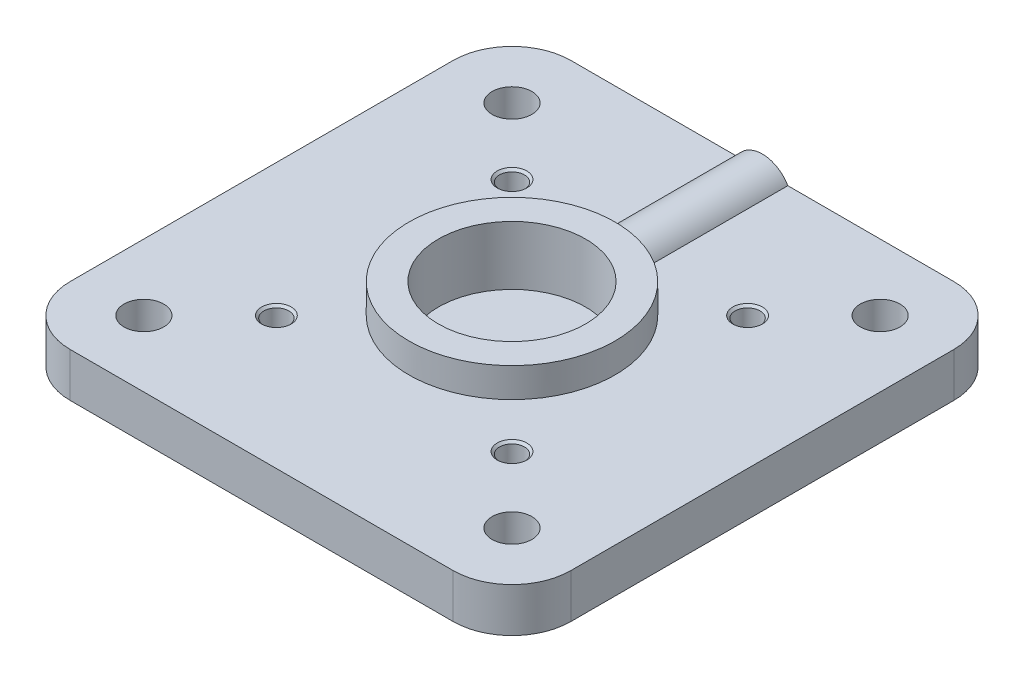
SolidWorks part; units mm, degrees
material "1060 Сплав"
ref_plane "Спереди" through (0, 0, 0) normal (0, 0, 1) x (1, 0, 0)
ref_plane "Сверху" through (0, 0, 0) normal (0, 1, 0) x (1, 0, 0)
ref_plane "Справа" through (0, 0, 0) normal (1, 0, 0) x (0, 0, -1)
sketch "Эскиз1" plane through (0, 0, 0) normal (0, 1, 0) x (1, 0, 0)
  line L1 (-65, -85) -> (65, -85)
  line L2 (-85, -65) -> (-85, 65)
  line L3 (-65, 85) -> (65, 85)
  line L4 (85, -65) -> (85, 65)
  line L5 (-85, -85) -> (85, 85) construction
  line L6 (-85, 85) -> (85, -85) construction
  arc A0 (-85, -65) -> (-65, -85) centre (-65, -65) ccw
  arc A1 (65, -85) -> (85, -65) centre (65, -65) ccw
  arc A2 (85, 65) -> (65, 85) centre (65, 65) ccw
  arc A3 (-65, 85) -> (-85, 65) centre (-65, 65) ccw
  point P0 (0, 0)
  dimension "D2" = 20
  dimension "D1" = 170
extrude "Бобышка-Вытянуть1" add sketch "Эскиз1" along normal blind 15
sketch "Эскиз2" plane through (0, 15, 0) normal (0, 1, 0) x (1, 0, 0)
  circle A0 centre (0, 0) radius 35
  dimension "D1" = 70
extrude "Бобышка-Вытянуть2" add sketch "Эскиз2" along normal blind 10
sketch "Эскиз3" plane through (0, 0, 0) normal (0, -1, 0) x (1, 0, 0)
  circle A0 centre (0, 0) radius 65
  circle A1 centre (0, 0) radius 50
  dimension "D1" = 130
  dimension "D2" = 100
extrude "Бобышка-Вытянуть3" add sketch "Эскиз3" along normal blind 10
sketch "Эскиз4" plane through (0, 25, 0) normal (0, 1, 0) x (1, 0, 0)
  circle A0 centre (0, 0) radius 25
  dimension "D1" = 50
extrude "Вырез-Вытянуть1" cut sketch "Эскиз4" against normal blind 20
sketch "Эскиз5" plane through (0, 15, 0) normal (0, 1, 0) x (1, 0, 0)
  line L1 (-62.5, -62.5) -> (62.5, -62.5) construction
  line L2 (-62.5, -62.5) -> (-62.5, 62.5) construction
  line L3 (-62.5, 62.5) -> (62.5, 62.5) construction
  line L4 (62.5, -62.5) -> (62.5, 62.5) construction
  line L5 (-62.5, -62.5) -> (62.5, 62.5) construction
  line L6 (-62.5, 62.5) -> (62.5, -62.5) construction
  circle A0 centre (-62.5, 62.5) radius 6.75
  circle A1 centre (62.5, 62.5) radius 6.75
  circle A2 centre (62.5, -62.5) radius 6.75
  circle A3 centre (-62.5, -62.5) radius 6.75
  point P0 (0, 0)
  dimension "D2" = 13.5
  dimension "D1" = 125
extrude "Вырез-Вытянуть2" cut sketch "Эскиз5" against normal up to next
sketch "Эскиз9" plane through (0, 0, -85) normal (0, 0, -1) x (-1, 0, 0)
  line L0 (0, -1000) -> (0, 49000) construction
  line L1 (-65, 0) -> (65, 0) construction
  circle A0 centre (0, 10) radius 10
  point P5 (0, 0)
  dimension "D1" = 20
extrude "Бобышка-Вытянуть4" add sketch "Эскиз9" against normal up to next
sketch "Эскиз10" plane through (0, 0, -85) normal (0, 0, -1) x (-1, 0, 0)
  line L0 (0, -1000) -> (0, 49000) construction
  line L1 (-65, 0) -> (65, 0) construction
  line L2 (-65, 0) -> (65, 0) construction
  circle A0 centre (0, 10) radius 6
  point P5 (0, 0)
  dimension "D1" = 12
  dimension "D2" = 10
ref_plane "Плоскость1" through (0, 0, -73) normal (0, 0, -1) x (-1, 0, 0)
sketch "Эскиз11" plane through (0, 0, -73) normal (0, 0, -1) x (-1, 0, 0)
  circle A3 centre (0, 10) radius 3
  circle A4 centre (0, 10) radius 3
  dimension "D1" = 3
loft "Вырез-По сечениям1" cut profiles "Эскиз11", "Эскиз10"
sketch "Эскиз12" plane through (0, 0, -73) normal (0, 0, -1) x (-1, 0, 0)
  circle A1 centre (0, 10) radius 3
  dimension "D1" = 6
extrude "Вырез-Вытянуть4" cut sketch "Эскиз12" against normal blind 33
sketch "Эскиз13" plane through (0, 0, 0) normal (0, -1, 0) x (1, 0, 0)
  line L0 (0, -1000) -> (0, 49000) construction
  line L1 (65, -85) -> (-65, -85) construction
  circle A0 centre (0, -43) radius 3
  dimension "D1" = 6
  dimension "D2" = 42
extrude "Вырез-Вытянуть5" cut sketch "Эскиз13" against normal blind 13
sketch "Эскиз14" plane through (0, 0, -40) normal (0, 0, -1) x (-1, 0, 0)
  line L0 (3, 10) -> (4.5, 10)
  line L1 (-3, 10) -> (-4.5, 10)
  arc A0 (3, 10) -> (-3, 10) centre (0, 10) ccw
  arc A1 (4.5, 10) -> (-4.5, 10) centre (0, 10) ccw
  dimension "D1" = 6
  dimension "D2" = 9
extrude "Бобышка-Вытянуть5" add sketch "Эскиз14" along normal blind 6
sketch "Эскиз15" plane through (0, 0, 0) normal (0, -1, 0) x (1, 0, 0)
  line L0 (-3, -43) -> (-4.5, -43)
  line L1 (3, -43) -> (4.5, -43)
  arc A0 (3, -43) -> (-3, -43) centre (0, -43) ccw
  arc A1 (4.5, -43) -> (-4.5, -43) centre (0, -43) ccw
  dimension "D1" = 6
  dimension "D2" = 9
extrude "Бобышка-Вытянуть6" add sketch "Эскиз15" against normal blind 13
sketch "Эскиз16" plane through (0, 15, 0) normal (0, 1, 0) x (1, 0, 0)
  line L1 (-40, -40) -> (40, -40) construction
  line L2 (-40, -40) -> (-40, 40) construction
  line L3 (-40, 40) -> (40, 40) construction
  line L4 (40, -40) -> (40, 40) construction
  line L5 (-40, -40) -> (40, 40) construction
  line L6 (-40, 40) -> (40, -40) construction
  point P0 (0, 0)
  dimension "D1" = 80
hole_wizard "Отверстие обработанное метчиком M10x1.52" positions "Трехмерный эскиз1" profile "Эскиз17" tap size "M10x1.5" standard "Ansi Metric"
sketch3d "Трехмерный эскиз1"
  point P0 (-40, 15, -40)
  point P3 (40, 15, -40)
  point P6 (40, 15, 40)
  point P9 (-40, 15, 40)
sketch "Эскиз17" plane through (-40, 15, -40) normal (1, 0, 0) x (0, 0, 1)
  line L0 (0, 0) -> (0, 20.5537)
  line L1 (0, 20.5537) -> (4.25, 18)
  line L2 (4.25, 18) -> (4.25, 0.775)
  line L3 (4.25, 0.775) -> (5.025, 0)
  line L5 (5.025, 0) -> (0, 0)
  line L6 (-4.25, 0.775) -> (-5.025, 0) construction
  line L10 (0, 20.5537) -> (-4.25, 18) construction
  line L11 (0, -6.35) -> (0, 107.95) construction
  dimension "Диаметр сверла" = 8.5
  dimension "Глубина сверла" = 18
  dimension "Диаметр передней зенковки" = 10.05
  dimension "Угол передней зенковки" = 90
  dimension "Угол заточки сверла" = 118
cosmetic thread "Отверстие резьбы5" parameters "D1"=14, "D2"=10
cosmetic thread "Отверстие резьбы6" parameters "D1"=14, "D2"=10
cosmetic thread "Отверстие резьбы7" parameters "D1"=14, "D2"=10
cosmetic thread "Отверстие резьбы8" parameters "D1"=14, "D2"=10
